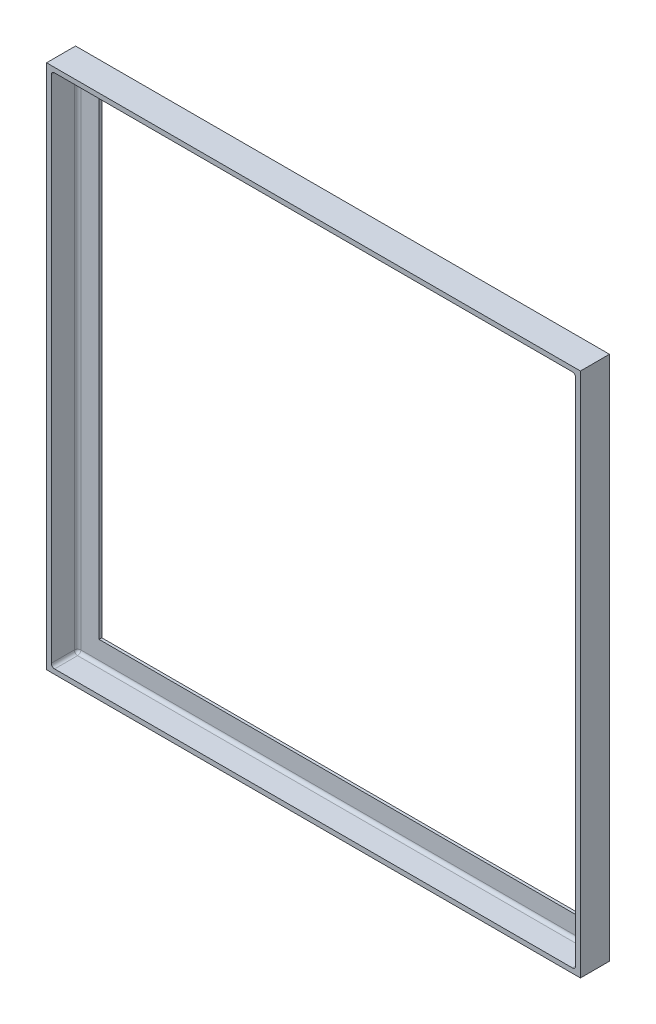
SolidWorks part; units mm, degrees
ref_plane "Front Plane" through (0, 0, 0) normal (0, 0, 1) x (1, 0, 0)
ref_plane "Top Plane" through (0, 0, 0) normal (0, 1, 0) x (1, 0, 0)
ref_plane "Right Plane" through (0, 0, 0) normal (1, 0, 0) x (0, 0, -1)
ref_plane "Plane1"
sketch "Sketch1" plane through (0, 0, 0) normal (0, 0, 1) x (1, 0, 0)
  line L0 (-257.9687, -254) -> (257.9688, -254)
  line L1 (257.9688, -254) -> (257.9687, 254)
  line L2 (257.9687, 254) -> (-257.9688, 254)
  line L3 (-257.9688, 254) -> (-257.9687, -254)
  line L4 (232.5688, -228.6) -> (-232.5687, -228.6)
  line L5 (-232.5687, -228.6) -> (-232.5688, 228.6)
  line L6 (-232.5688, 228.6) -> (232.5687, 228.6)
  line L7 (232.5687, 228.6) -> (232.5688, -228.6)
  dimension "D1" = 515.9375
  dimension "D2" = 508
  dimension "D3" = 25.4
extrude "Extrusion1" add sketch "Sketch1" along normal blind 2.6568 contours L2 L3 L0 L1 L6 L7 L4 L5
ref_plane "Plane2"
sketch "Sketch2" plane through (0, 0, 2.6568) normal (0, 0, 1) x (1, 0, 0)
  line L0 (-257.9688, 254) -> (257.9688, 254)
  line L1 (257.9688, 254) -> (257.9688, -254)
  line L2 (257.9688, -254) -> (-257.9688, -254)
  line L3 (-257.9688, -254) -> (-257.9688, 254)
  line L4 (-253.3831, -249.4144) -> (253.3831, -249.4144)
  line L5 (253.3831, -249.4144) -> (253.3831, 249.4144)
  line L6 (253.3831, 249.4144) -> (-253.3831, 249.4144)
  line L7 (-253.3831, 249.4144) -> (-253.3831, -249.4144)
extrude "Extrusion2" add sketch "Sketch2" along normal blind 25.4 contours L3 L2 L1 L0 L7 L6 L5 L4
fillet "Fillet1" radius 3.175 8 edges at (-253.3831, 249.4144, 15.3568) (253.3831, 249.4144, 15.3568) (0, 249.4144, 2.6568) (253.3831, -249.4144, 15.3568) (253.3831, 0, 2.6568) (-253.3831, -249.4144, 15.3568) (0, -249.4144, 2.6568) (-253.3831, 0, 2.6568)
